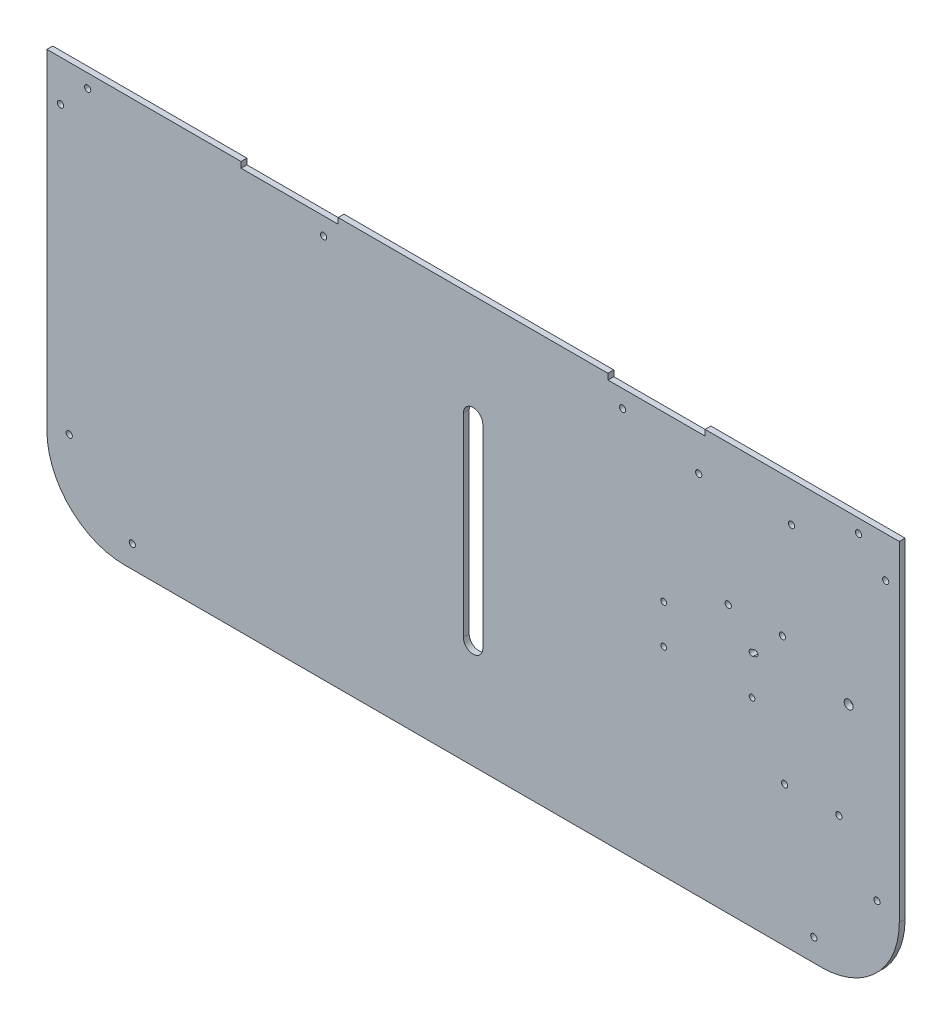
SolidWorks part; units mm, degrees
ref_plane "Plan de face" through (0, 0, 0) normal (0, 0, 1) x (1, 0, 0)
ref_plane "Plan de dessus" through (0, 0, 0) normal (0, 1, 0) x (1, 0, 0)
ref_plane "Plan de droite" through (0, 0, 0) normal (1, 0, 0) x (0, 0, -1)
sketch "Esquisse1" plane through (0, 0, 0) normal (0, 0, 1) x (1, 0, 0)
  line L1 (219.5, -105) -> (-219.5, -105)
  line L2 (219.5, -105) -> (219.5, 105)
  line L3 (219.5, 105) -> (-219.5, 105)
  line L4 (-219.5, -105) -> (-219.5, 105)
  line L5 (219.5, -105) -> (-219.5, 105) construction
  line L6 (219.5, 105) -> (-219.5, -105) construction
  point P0 (0, 0)
  dimension "D1" = 439
  dimension "D2" = 210
extrude "Boss.-Extru.1" add sketch "Esquisse1" along normal blind 3
sketch "Esquisse5" plane through (0, 0, 0) normal (0, 0, -1) x (-1, 0, 0)
  circle A0 centre (-145.2167, 18.0104) radius 1.4774
  circle A1 centre (-160.4356, -32.78) radius 1.5984
  circle A2 centre (-188.38, -32.79) radius 1.5875
  circle A3 centre (-193.46, 19.28) radius 2.3147
extrude "Enlèv. mat.-Extru.3" cut sketch "Esquisse5" against normal blind 4
sketch "Esquisse7" plane through (0, 0, 3) normal (0, 0, 1) x (1, 0, 0)
  line L0 (218.3793, -56.7403) -> (218.3793, -48.5264)
  line L1 (0, -159.4844) -> (0, 198.2871) construction
  line L2 (-217.5, -30.0053) -> (-249.9982, -30.0053) construction
  line L3 (219.5, -105) -> (219.5, 105) construction
  line L4 (217.5, -7.3773) -> (217.5, -52.6333) construction
  line L5 (217.5, -30.0053) -> (249.9982, -30.0053) construction
  line L6 (218.3793, -3.2704) -> (218.3793, -11.4842)
  line L7 (-217.5, -7.3773) -> (-217.5, -52.6333) construction
  line L8 (-218.3793, -3.2704) -> (-218.3793, -11.4842)
  line L9 (-218.3793, -56.7403) -> (-218.3793, -48.5264)
  line L10 (63.7, -103) -> (55.3, -103)
  line L11 (-63.7, -103) -> (-55.3, -103)
  line L12 (-219.5, -105) -> (219.5, -105) construction
  line L13 (-249.9982, 0) -> (281.4305, 0) construction
  line L14 (63.7, 103) -> (55.3, 103)
  line L15 (-63.7, 103) -> (-55.3, 103)
  line L16 (219.5, 74.5456) -> (0, 74.5456) construction
  line L17 (109.75, 74.5456) -> (109.75, 208.4684) construction
  line L18 (155.8, 103) -> (164.2, 103)
  line L19 (0, 74.5456) -> (-219.5, 74.5456) construction
  line L20 (-219.5, 105) -> (-219.5, -105) construction
  line L21 (-109.75, 74.5456) -> (-109.75, 208.4684) construction
  line L22 (-155.8, 103) -> (-164.2, 103)
  arc A0 (218.3793, -11.4842) -> (218.3793, -3.2704) centre (217.5, -7.3773) ccw
  arc A1 (218.3793, -48.5264) -> (218.3793, -56.7403) centre (217.5, -52.6333) cw
  arc A2 (-218.3793, -48.5264) -> (-218.3793, -56.7403) centre (-217.5, -52.6333) ccw
  arc A3 (-218.3793, -11.4842) -> (-218.3793, -3.2704) centre (-217.5, -7.3773) cw
  arc A4 (-55.3, -103) -> (-63.7, -103) centre (-59.5, -103) cw
  arc A5 (55.3, 103) -> (63.7, 103) centre (59.5, 103) cw
  arc A8 (-55.3, 103) -> (-63.7, 103) centre (-59.5, 103) ccw
  arc A10 (55.3, -103) -> (63.7, -103) centre (59.5, -103) ccw
  arc A11 (164.2, 103) -> (155.8, 103) centre (160, 103) ccw
  arc A12 (-164.2, 103) -> (-155.8, 103) centre (-160, 103) cw
  dimension "D1" = 4.2
  dimension "D2" = 2
  dimension "D3" = 4.2
  dimension "D5" = 4.2
  dimension "D6" = 2
  dimension "D7" = 160
  dimension "D4" = 2
extrude "Boss.-Extru.2" [suppressed] add sketch "Esquisse7" against normal through all
sketch "Esquisse9" [suppressed] plane through (0, 0, 3) normal (0, 0, 1) x (1, 0, 0)
  line L0 (0, -136.029) -> (0, 150.2761) construction
  circle A0 centre (59.5, -103) radius 1.6
  circle A1 centre (217.5, -52.6333) radius 1.6
  circle A2 centre (217.5, -7.3773) radius 1.6
  circle A3 centre (-217.5, -7.3773) radius 1.6
  circle A4 centre (-217.5, -52.6333) radius 1.6
  circle A5 centre (-59.5, -103) radius 1.6
  circle A6 centre (160, 103) radius 1.6
  circle A7 centre (59.5, 103) radius 1.6
  circle A8 centre (-59.5, 103) radius 1.6
  circle A9 centre (-160, 103) radius 1.6
  dimension "D1" = 3.2
  dimension "D2" = 3.2
  dimension "D3" = 3.2
  dimension "D4" = 3.2
  dimension "D5" = 3.2
  dimension "D6" = 3.2
  dimension "D7" = 3.2
extrude "Enlèv. mat.-Extru.4" [suppressed] cut sketch "Esquisse9" against normal through all
sketch "Esquisse10" plane through (0, 0, 3) normal (0, 0, 1) x (1, 0, 0)
  line L0 (219.5, 105) -> (-219.5, 105) construction
  line L1 (-119.5, 102) -> (-69.5, 102)
  line L2 (-119.5, 102) -> (-119.5, 105)
  line L3 (-119.5, 105) -> (-69.5, 105)
  line L4 (-69.5, 102) -> (-69.5, 105)
  line L5 (-69.5, 102) -> (-69.5, 105) construction
  line L6 (69.5, 102) -> (69.5, 105) construction
  line L7 (119.5, 102) -> (69.5, 102)
  line L8 (119.5, 102) -> (119.5, 105)
  line L9 (119.5, 105) -> (69.5, 105)
  line L10 (69.5, 102) -> (69.5, 105)
extrude "Enlèv. mat.-Extru.5" cut sketch "Esquisse10" against normal blind 4
sketch "Esquisse11" plane through (0, 0, 3) normal (0, 0, 1) x (1, 0, 0)
  line L0 (0, -50) -> (0, 50) construction
  line L1 (-5, -50) -> (-5, 50)
  line L2 (5, -50) -> (5, 50)
  arc A0 (-5, -50) -> (5, -50) centre (0, -50) ccw
  arc A1 (5, 50) -> (-5, 50) centre (0, 50) ccw
  point P3 (0, 0)
  point P8 (-5, 0)
  dimension "D2" = 5
  dimension "D1" = 100
extrude "Enlèv. mat.-Extru.6" cut sketch "Esquisse11" against normal through all
fillet "Fillet1" radius 40 2 edges at (219.5, -105, 1.5) (-219.5, -105, 1.5)
sketch "Sketch1" plane through (0, 0, 0) normal (0, 0, -1) x (-1, 0, 0)
  circle A0 centre (-208, -61) radius 1.6
extrude "Cut-Extrude1" cut sketch "Sketch1" against normal through all
sketch "Sketch2" plane through (0, 0, 0) normal (0, 0, -1) x (-1, 0, 0)
  circle A0 centre (208, -61) radius 1.6
  circle A1 centre (175.5, -93.5) radius 1.6
extrude "Cut-Extrude2" cut sketch "Sketch2" against normal through all
sketch "Sketch3" plane through (0, 0, 0) normal (0, 0, -1) x (-1, 0, 0)
  circle A0 centre (-175.5, -93.5) radius 1.6
extrude "Cut-Extrude3" cut sketch "Sketch3" against normal through all
sketch "Sketch4" plane through (0, 0, 0) normal (0, 0, -1) x (-1, 0, 0)
  circle A0 centre (-198.5, 98) radius 1.6
  circle A1 centre (-212.5, 84) radius 1.6
  circle A2 centre (198.5, 98) radius 1.6
  circle A3 centre (212.5, 84) radius 1.6
extrude "Cut-Extrude4" cut sketch "Sketch4" against normal through all
sketch "Sketch5" plane through (0, 0, 0) normal (0, 0, -1) x (-1, 0, 0)
  circle A0 centre (77, 93) radius 1.6
  circle A1 centre (-77, 93) radius 1.6
extrude "Cut-Extrude5" cut sketch "Sketch5" against normal through all
sketch "Sketch7" plane through (0, 0, 0) normal (0, 0, -1) x (-1, 0, 0)
  circle A0 centre (-131.4, 32.8) radius 1.6
  circle A1 centre (-159.3, 32.8) radius 1.6
  circle A2 centre (-116.2, 83.6) radius 1.6
  circle A3 centre (-164, 84.7) radius 1.6
  dimension "D1" = 3.2
extrude "Cut-Extrude6" cut sketch "Sketch7" against normal through all
sketch "Sketch8" plane through (0, 0, 0) normal (0, 0, -1) x (-1, 0, 0)
  circle A0 centre (-98.175, -2.55) radius 1.475
  circle A1 centre (-98.175, 17.45) radius 1.475
  circle A2 centre (-143.675, 17.45) radius 1.475
  circle A3 centre (-143.675, -2.55) radius 1.475
extrude "Cut-Extrude7" cut sketch "Sketch8" against normal through all
